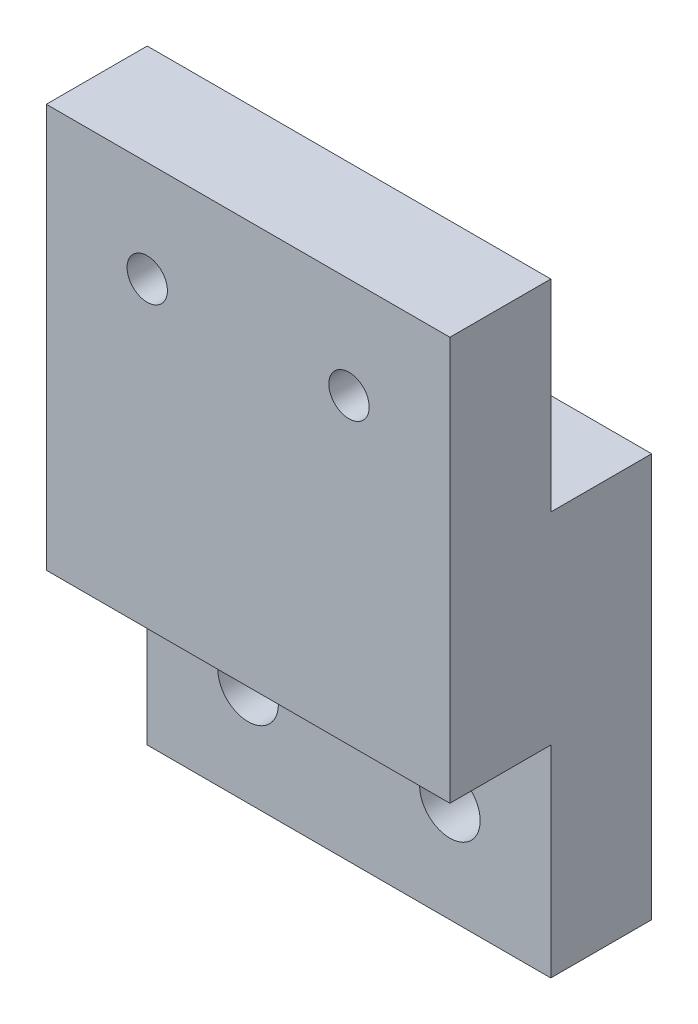
SolidWorks part; units mm, degrees
ref_plane "Front Plane" through (0, 0, 0) normal (0, 0, 1) x (1, 0, 0)
ref_plane "Top Plane" through (0, 0, 0) normal (0, 1, 0) x (1, 0, 0)
ref_plane "Right Plane" through (0, 0, 0) normal (1, 0, 0) x (0, 0, -1)
sketch "Sketch1" plane through (0, 0, 0) normal (0, 0, 1) x (1, 0, 0)
  line L1 (10, 5) -> (-10, 5)
  line L2 (10, 5) -> (10, -5)
  line L3 (10, -5) -> (-10, -5)
  line L4 (-10, 5) -> (-10, -5)
  line L5 (10, 5) -> (-10, -5) construction
  line L6 (10, -5) -> (-10, 5) construction
  point P0 (0, 0)
extrude "Boss-Extrude1" add sketch "Sketch1" along normal blind 5
sketch "Sketch2" plane through (0, -5, 0) normal (0, -1, 0) x (1, 0, 0)
  line L1 (-10, 5) -> (10, 5)
  line L2 (-10, 5) -> (-10, 0)
  line L3 (-10, 0) -> (10, 0)
  line L4 (10, 5) -> (10, 0)
extrude "Boss-Extrude2" add sketch "Sketch2" along normal blind 10
sketch "Sketch3" plane through (0, 0, 0) normal (0, 0, -1) x (-1, 0, 0)
  line L0 (-10, -15) -> (-10, 5) construction
  line L1 (10, -15) -> (-10, -15)
  line L2 (10, -15) -> (10, -5)
  line L3 (10, -5) -> (-10, -5)
  line L4 (-10, -15) -> (-10, -5)
extrude "Boss-Extrude3" add sketch "Sketch3" along normal blind 5
sketch "Sketch5" plane through (0, 0, 5) normal (0, 0, 1) x (1, 0, 0)
  line L0 (-10, 5) -> (-10, -5) construction
  line L1 (-10, 5) -> (-10, -15) construction
  line L2 (-10, -5) -> (-5, -5) construction
  line L3 (-5, -5) -> (5, -5) construction
  line L4 (5, -5) -> (5, 0) construction
  line L5 (-5, -5) -> (-5, 0) construction
  circle A0 centre (-5, 0) radius 1
  circle A1 centre (5, 0) radius 1
extrude "Cut-Extrude1" cut sketch "Sketch5" against normal blind 10
sketch "Sketch7" plane through (0, -15, 0) normal (0, -1, 0) x (1, 0, 0)
  line L0 (10, -5) -> (10, 5) construction
  line L1 (-10, -5) -> (10, -5)
  line L2 (-10, -5) -> (-10, 0)
  line L3 (-10, 0) -> (10, 0)
  line L4 (10, -5) -> (10, 0)
extrude "Boss-Extrude5" add sketch "Sketch7" along normal blind 10
sketch "Sketch8" plane through (0, 0, 0) normal (0, 0, 1) x (1, 0, 0)
  line L0 (0, -25) -> (-5, -25) construction
  line L1 (10, -25) -> (-10, -25) construction
  line L2 (-5, -25) -> (-5, -20) construction
  line L3 (0, -25) -> (5, -25) construction
  line L4 (5, -25) -> (5, -20) construction
  circle A0 centre (-5, -20) radius 1.5
  circle A1 centre (5, -20) radius 1.5
extrude "Cut-Extrude3" cut sketch "Sketch8" against normal blind 10
